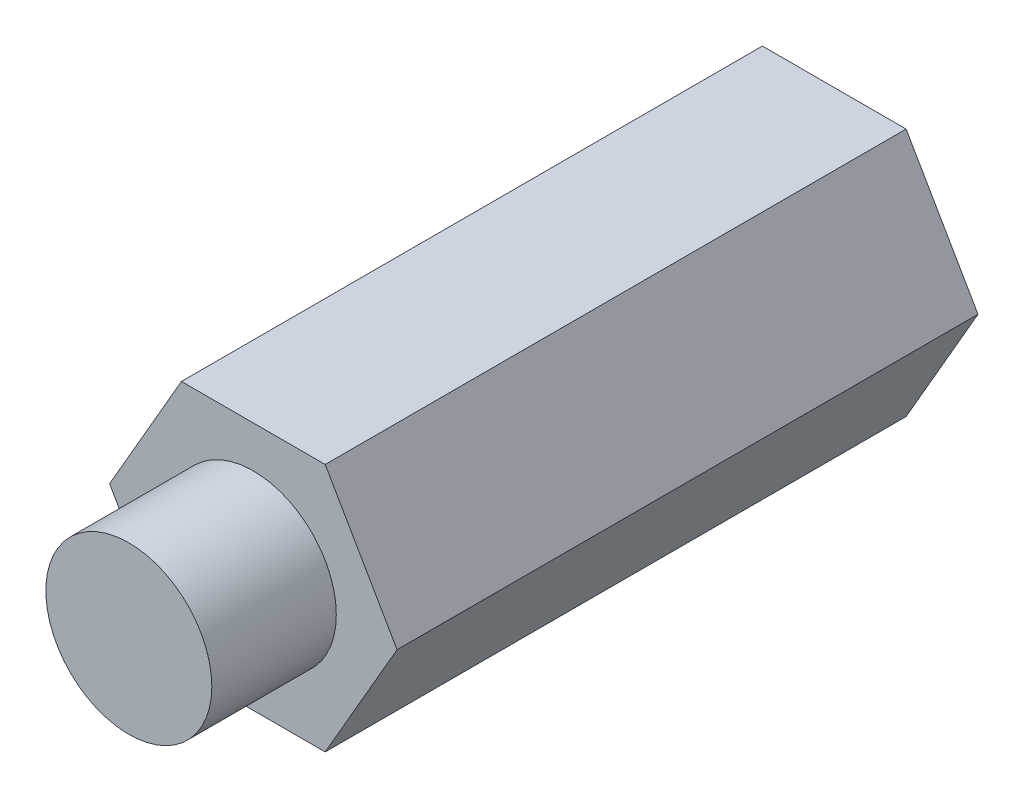
SolidWorks part; units mm, degrees
ref_plane "Front Plane" through (0, 0, 0) normal (0, 0, 1) x (1, 0, 0)
ref_plane "Top Plane" through (0, 0, 0) normal (0, 1, 0) x (1, 0, 0)
ref_plane "Right Plane" through (0, 0, 0) normal (1, 0, 0) x (0, 0, -1)
sketch "Sketch1" plane through (0, 0, 0) normal (0, 0, 1) x (1, 0, 0)
  line L1 (1.7321, 3) -> (-1.7321, 3)
  line L2 (-1.7321, 3) -> (-3.4641, 0)
  line L3 (-3.4641, 0) -> (-1.7321, -3)
  line L4 (-1.7321, -3) -> (1.7321, -3)
  line L5 (1.7321, -3) -> (3.4641, 0)
  line L6 (3.4641, 0) -> (1.7321, 3)
  circle A0 centre (0, 0) radius 3 construction
  dimension "D1" = 6
extrude "Boss-Extrude1" add sketch "Sketch1" along normal blind 14
sketch "Sketch2" plane through (0, 0, 14) normal (0, 0, 1) x (1, 0, 0)
  circle A0 centre (0, 0) radius 2
  dimension "D1" = 4
extrude "Boss-Extrude2" add sketch "Sketch2" along normal blind 3
hole_wizard "Ø3.0mm Dowel Hole1" positions "Sketch4" profile "Sketch5" hole size "Ø3.0" standard "ANSI Metric"
sketch "Sketch4" plane through (0, 0, 0) normal (0, 0, -1) x (-1, 0, 0)
  point P0 (0, 0)
sketch "Sketch5" plane through (0, 0, 0) normal (1, 0, 0) x (0, 1, 0)
  line L0 (0, 0) -> (0, 6.9013)
  line L1 (0, 6.9013) -> (1.5, 6)
  line L2 (1.5, 6) -> (1.5, 0)
  line L5 (1.5, 0) -> (0, 0)
  line L10 (0, 6.9013) -> (-1.5, 6) construction
  line L11 (0, -6.35) -> (0, 107.95) construction
  dimension "Hole Dia." = 3
  dimension "Hole Depth" = 6
  dimension "Drill Angle" = 118
